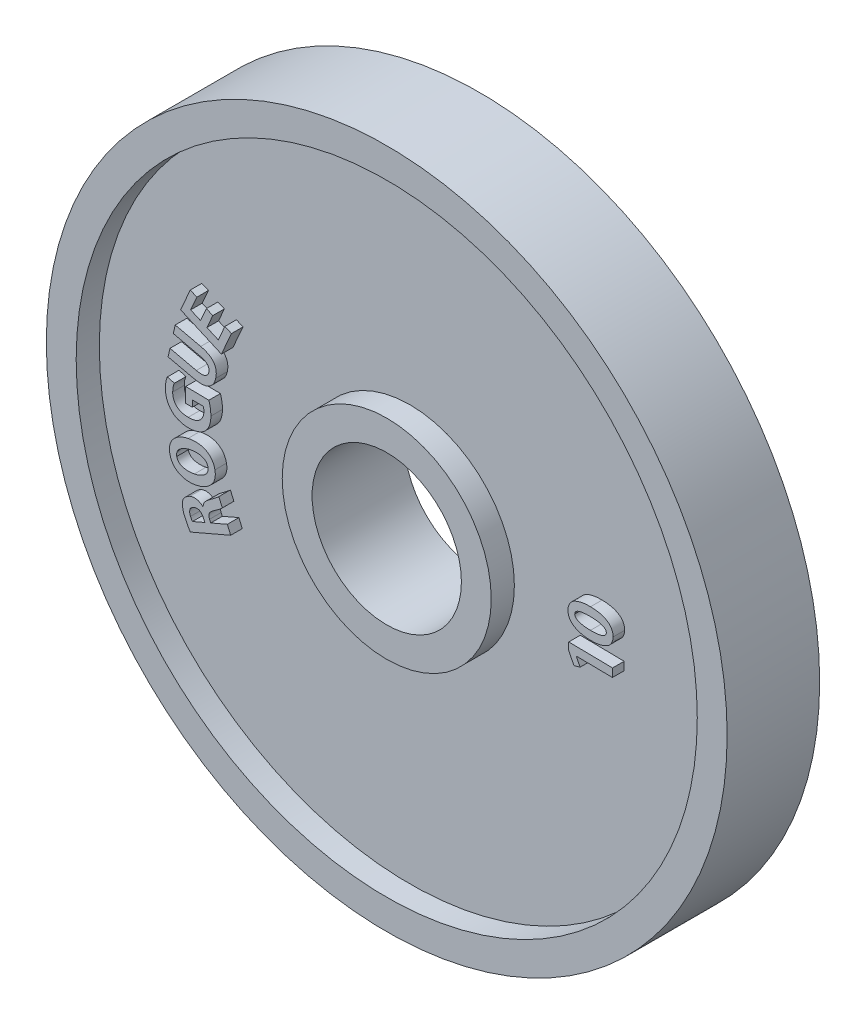
SolidWorks part; units mm, degrees
ref_plane "Front Plane" through (0, 0, 0) normal (0, 0, 1) x (1, 0, 0)
ref_plane "Top Plane" through (0, 0, 0) normal (0, 1, 0) x (1, 0, 0)
ref_plane "Right Plane" through (0, 0, 0) normal (1, 0, 0) x (0, 0, -1)
sketch "Sketch1" plane through (0, 0, 0) normal (0, 0, 1) x (1, 0, 0)
  circle A0 centre (0, 0) radius 114
  circle A1 centre (0, 0) radius 25
  dimension "D1" = 228
  dimension "D2" = 50
extrude "Boss-Extrude1" add sketch "Sketch1" along normal mid plane 30.988
sketch "Sketch2" plane through (0, 0, 15.494) normal (0, 0, 1) x (1, 0, 0)
  circle A0 centre (0, 0) radius 35
  circle A1 centre (0, 0) radius 104
  circle A3 centre (0, 0) radius 114 construction
  dimension "D1" = 10
  dimension "D2" = 35
extrude "Cut-Extrude1" cut sketch "Sketch2" against normal blind 7.747
sketch "Sketch3" plane through (0, 0, 7.747) normal (0, 0, 1) x (1, 0, 0)
  text T0 "ROGUE" font "Adobe Gothic Std B" height in points 48
extrude "Boss-Extrude2" add sketch "Sketch3" along normal blind 3.8735
sketch "Sketch4" plane through (0, 0, 7.747) normal (0, 0, 1) x (1, 0, 0)
  text T0 "10" font "Adobe Gothic Std B" height in points 48
extrude "Boss-Extrude3" add sketch "Sketch4" along normal blind 3.8735
mirror "Mirror1" about plane through (0, 0, 0) normal (0, 0, 1) of "Cut-Extrude1"
